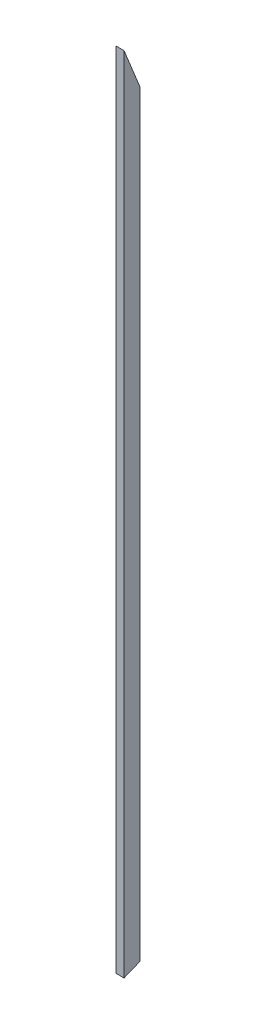
SolidWorks part; units mm, degrees
ref_plane "Спереди" through (0, 0, 0) normal (0, 0, 1) x (1, 0, 0)
ref_plane "Сверху" through (0, 0, 0) normal (0, 1, 0) x (1, 0, 0)
ref_plane "Справа" through (0, 0, 0) normal (1, 0, 0) x (0, 0, -1)
other "Configuration Table"
sketch "Эскиз1" plane through (0, 0, 0) normal (0, 1, 0) x (1, 0, 0)
  line L1 (12.5, 25) -> (-12.5, 25)
  line L2 (12.5, 25) -> (12.5, -25)
  line L3 (12.5, -25) -> (-12.5, -25)
  line L4 (-12.5, 25) -> (-12.5, -25)
  line L5 (12.5, 25) -> (-12.5, -25) construction
  line L6 (12.5, -25) -> (-12.5, 25) construction
  point P0 (0, 0)
extrude "Бобышка-Вытянуть1" add sketch "Эскиз1" along normal blind 2534.7584
sketch "Эскиз2" plane through (12.5, 0, 0) normal (1, 0, 0) x (0, 0, -1)
  line L0 (25, 0) -> (25, 20.2128)
  line L1 (25, 2534.7584) -> (25, 0) construction
  line L2 (25, 20.2128) -> (-25, 0)
  line L3 (-25, 0) -> (25, 0)
  line L4 (25, 2534.7584) -> (25, 2411.0742)
  line L5 (25, 2411.0742) -> (-25, 2534.7584)
  line L6 (-25, 2534.7584) -> (25, 2534.7584)
extrude "Вырез-Вытянуть1" cut sketch "Эскиз2" against normal blind 2534.7584
